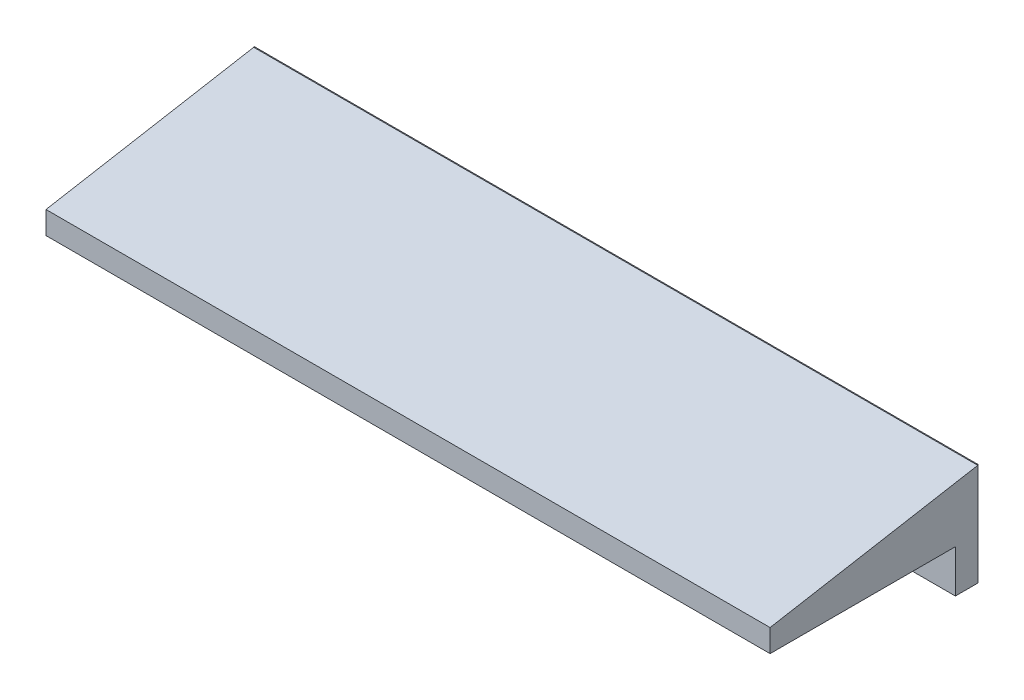
SolidWorks part; units mm, degrees
ref_plane "Front" through (0, 0, 0) normal (0, 0, 1) x (1, 0, 0)
ref_plane "Top" through (0, 0, 0) normal (0, 1, 0) x (1, 0, 0)
ref_plane "Right" through (0, 0, 0) normal (1, 0, 0) x (0, 0, -1)
sketch "Sketch1" plane through (0, 0, 0) normal (0, 1, 0) x (1, 0, 0)
  line L1 (-50.8, -13) -> (50.8, -13)
  line L2 (-50.8, -13) -> (-50.8, 13)
  line L3 (-50.8, 13) -> (50.8, 13)
  line L4 (50.8, -13) -> (50.8, 13)
  line L5 (-50.8, -13) -> (50.8, 13) construction
  line L6 (-50.8, 13) -> (50.8, -13) construction
  point P0 (0, 0)
  dimension "D1" = 26
  dimension "D2" = 101.6
extrude "Boss-Extrude1" add sketch "Sketch1" along normal blind 3.175
sketch "Sketch2" plane through (0, 0, -13) normal (0, 0, -1) x (-1, 0, 0)
  line L0 (50.8, 3.175) -> (-50.8, 3.175)
  line L1 (50.8, 3.175) -> (50.8, -6)
  line L2 (-50.8, 3.175) -> (-50.8, -6)
  line L3 (50.8, -6) -> (-50.8, -6)
  dimension "D1" = 9.175
extrude "Boss-Extrude2" add sketch "Sketch2" along normal blind 3.175
sketch "Sketch3" plane through (0, 0, -13) normal (0, 0, 1) x (1, 0, 0)
  line L0 (50.8, -3) -> (-50.8, -3)
  line L1 (50.8, 0) -> (50.8, -6) construction
  line L2 (-50.8, -6) -> (-50.8, 0) construction
  circle A0 centre (30.3075, -3) radius 1.6
  circle A1 centre (-30.3075, -3) radius 1.6
  circle A2 centre (43.9685, -3) radius 1.6
  circle A3 centre (-43.9685, -3) radius 1.6
  point P10 (0, -3)
  dimension "D3" = 13.661
  dimension "D1" = 30.3075
  dimension "D2" = 30.3075
  dimension "D4" = 13.661
extrude "Cut-Extrude1" cut sketch "Sketch3" against normal blind 3.175 contours A3 | A1 | A2 | A0
sketch "Sketch4" plane through (50.8, 0, 0) normal (1, 0, 0) x (0, 0, -1)
  line L0 (-13, 3.175) -> (16.1432, 8.3137)
  line L1 (-13, 3.175) -> (16.175, 3.175) construction
  line L2 (16.175, 3.175) -> (16.175, 8.4128)
  line L3 (16.175, 3.175) -> (-13, 3.175)
  line L4 (16.175, 8.4128) -> (16.1432, 8.3137)
  line L9 (-13, 0) -> (13, 0)
  line L10 (13, 0) -> (13, -6)
  line L11 (13, -6) -> (16.175, -6)
  line L12 (16.175, -6) -> (16.175, 3.175)
  line L13 (16.175, 3.175) -> (-13, 3.175)
  line L14 (-13, 3.175) -> (-13, 0)
  line L15 (-13, 0) -> (13, 0)
  line L16 (13, 0) -> (13, -6)
  line L17 (13, -6) -> (16.175, -6)
  line L18 (16.175, -6) -> (16.175, 3.175)
  line L20 (-13, 3.175) -> (-13, 0)
  line M6 (16.175, 3.175) -> (-13, 3.175)
  dimension "D1" = 10
  dimension "D2" = 0
extrude "Boss-Extrude3" add sketch "Sketch4" against normal blind 101.6 contours L2 L4 L0 M6
